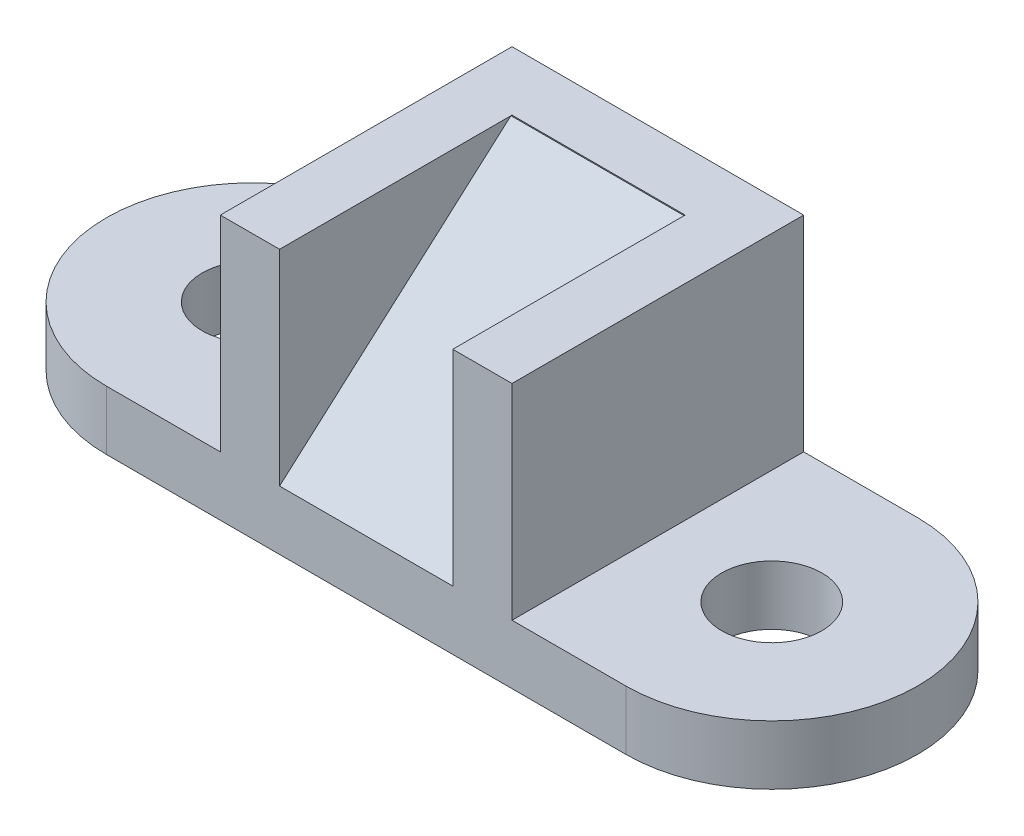
SolidWorks part; units mm, degrees
ref_plane "Front Plane" through (0, 0, 0) normal (0, 0, 1) x (1, 0, 0)
ref_plane "Top Plane" through (0, 0, 0) normal (0, 1, 0) x (1, 0, 0)
ref_plane "Right Plane" through (0, 0, 0) normal (1, 0, 0) x (0, 0, -1)
sketch "Sketch2" plane through (0, 0, 0) normal (0, 1, 0) x (1, 0, 0)
  line L0 (0, 48.967) -> (0, -48.967) construction
  line L1 (57, 32) -> (-57, 32)
  line L2 (-84.8591, 0) -> (84.8591, 0) construction
  line L3 (57, -32) -> (-57, -32)
  arc A0 (-57, 32) -> (-57, -32) centre (-57, 0) ccw
  circle A1 centre (-57, 0) radius 11
  circle A2 centre (57, 0) radius 11
  arc A3 (57, 32) -> (57, -32) centre (57, 0) cw
  point P4 (0, 0)
  point P10 (0, 0)
  point P15 (0, -32)
  point P18 (0, 32)
  dimension "D2" = 32
  dimension "D3" = 22
  dimension "D1" = 57
extrude "Boss-Extrude1" add sketch "Sketch2" along normal blind 58
sketch "Sketch3" plane through (0, 58, 0) normal (0, 1, 0) x (1, 0, 0)
  line L0 (0, 49.3924) -> (0, -49.3924) construction
  line L1 (-32, 32) -> (-32, -32)
  line L2 (57, 32) -> (-57, 32) construction
  line L3 (-57, -32) -> (57, -32) construction
  line L4 (32, 32) -> (32, -32)
  line L5 (-32, 32) -> (-57, 32)
  line L6 (-32, -32) -> (-57, -32)
  line L7 (32, -32) -> (57, -32)
  line L8 (32, 32) -> (57, 32)
  arc A2 (-57, 32) -> (-57, -32) centre (-57, 0) ccw
  arc A3 (57, 32) -> (57, -32) centre (57, 0) cw
  point P4 (0, 0)
  dimension "D1" = 32
extrude "Cut-Extrude1" cut sketch "Sketch3" against normal blind 45
sketch "Sketch4" plane through (0, 58, 0) normal (0, 1, 0) x (1, 0, 0)
  line L0 (-19, 19) -> (-19, -32)
  line L1 (-32, -32) -> (32, -32) construction
  line L5 (-19, -32) -> (19, -32)
  line L6 (19, -32) -> (19, 19)
  line L7 (19, 19) -> (-19, 19)
extrude "Cut-Extrude7" cut sketch "Sketch4" against normal blind 45
sketch "Sketch6" plane through (-19, 0, 0) normal (1, 0, 0) x (0, 0, -1)
  line L0 (18.7656, 58) -> (-32, 13)
  line L1 (32, 58) -> (-32, 58) construction
  line L2 (-32, 13) -> (18.7656, 13)
  line L3 (32, 13) -> (-32, 13) construction
  line L4 (18.7656, 13) -> (18.7656, 58)
extrude "Boss-Extrude2" add sketch "Sketch6" along normal blind 45
